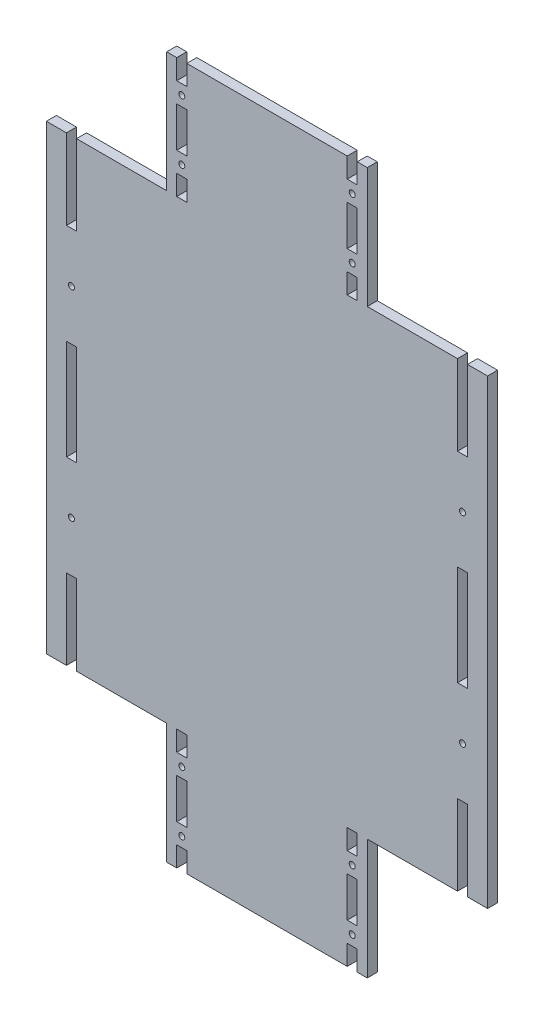
SolidWorks part; units mm, degrees
ref_plane "Front Plane" through (0, 0, 0) normal (0, 0, 1) x (1, 0, 0)
ref_plane "Top Plane" through (0, 0, 0) normal (0, 1, 0) x (1, 0, 0)
ref_plane "Right Plane" through (0, 0, 0) normal (1, 0, 0) x (0, 0, -1)
sketch "Sketch1" plane through (0, 0, 0) normal (0, 0, 1) x (1, 0, 0)
  line L1 (-110, 175) -> (110, 175)
  line L2 (-110, 175) -> (-110, -175)
  line L3 (-110, -175) -> (110, -175)
  line L4 (110, 175) -> (110, -175)
  line L5 (-110, 175) -> (110, -175) construction
  line L6 (-110, -175) -> (110, 175) construction
  point P0 (0, 0)
  dimension "D1" = 220
  dimension "D2" = 350
extrude "Boss-Extrude1" add sketch "Sketch1" along normal blind 5
sketch "Sketch2" plane through (0, 0, 5) normal (0, 0, 1) x (1, 0, 0)
  line L0 (0, 175) -> (0, -175) construction
  line L1 (110, 175) -> (-110, 175) construction
  line L2 (-110, -175) -> (110, -175) construction
  line L3 (-110, 0) -> (110, 0) construction
  line L4 (-110, 175) -> (-110, -175) construction
  line L5 (110, -175) -> (110, 175) construction
  line L6 (-110, 115) -> (110, 115) construction
  line L7 (-110, -115) -> (110, -115) construction
  line L8 (-50, 175) -> (-50, -175) construction
  line L9 (50, 175) -> (50, -175) construction
  line L10 (-110, -115) -> (-50, -115)
  line L11 (-110, -175) -> (-110, -115)
  line L12 (110, -115) -> (50, -115)
  line L13 (50, -115) -> (50, -175)
  line L14 (50, -175) -> (110, -175)
  line L15 (110, -175) -> (110, -115)
  line L16 (50, 175) -> (50, 115)
  line L17 (50, 115) -> (110, 115)
  line L18 (110, 115) -> (110, 175)
  line L19 (110, 175) -> (50, 175)
  line L20 (-110, 175) -> (-50, 175)
  line L21 (-50, 175) -> (-50, 115)
  line L22 (-50, 115) -> (-110, 115)
  line L23 (-110, 115) -> (-110, 175)
  line L24 (-50, -115) -> (-50, -175)
  line L25 (-50, -175) -> (-110, -175)
  dimension "D1" = 60
  dimension "D2" = 60
  dimension "D3" = 60
  dimension "D4" = 60
extrude "Cut-Extrude2" cut sketch "Sketch2" against normal blind 5
sketch "Sketch3" plane through (0, 0, 5) normal (0, 0, 1) x (1, 0, 0)
  line L0 (0, 175) -> (0, -175) construction
  line L2 (-50, -175) -> (50, -175) construction
  line L27 (50, 175) -> (-50, 175) construction
  line L32 (-45, 175) -> (-45, -175) construction
  line L33 (45, 175) -> (45, -175) construction
  line L34 (-50, -115) -> (50, -115) construction
  line L35 (-50, 115) -> (50, 115) construction
  line L37 (-45, 175) -> (-40, 175)
  line L38 (-45, 175) -> (-45, 115)
  line L39 (-45, 115) -> (-40, 115)
  line L40 (-40, 175) -> (-40, 115)
  line L41 (45, 175) -> (40, 175)
  line L42 (45, 175) -> (45, 115)
  line L43 (45, 115) -> (40, 115)
  line L44 (40, 175) -> (40, 115)
  line L45 (-45, -175) -> (-40, -175)
  line L46 (-45, -175) -> (-45, -115)
  line L47 (-45, -115) -> (-40, -115)
  line L48 (-40, -175) -> (-40, -115)
  line L49 (45, -175) -> (40, -175)
  line L50 (45, -175) -> (45, -115)
  line L51 (45, -115) -> (40, -115)
  line L52 (40, -175) -> (40, -115)
  line L53 (-45, 175) -> (-40, 175)
  line L54 (-45, 175) -> (-45, 165)
  line L55 (-45, 165) -> (-40, 165)
  line L56 (-40, 175) -> (-40, 165)
  line L57 (-45, 155) -> (-40, 155)
  line L58 (-45, 155) -> (-45, 135)
  line L59 (-45, 135) -> (-40, 135)
  line L60 (-40, 155) -> (-40, 135)
  line L61 (-45, 125) -> (-40, 125)
  line L62 (-45, 125) -> (-45, 115)
  line L63 (-45, 115) -> (-40, 115)
  line L64 (-40, 125) -> (-40, 115)
  line L65 (40, 175) -> (45, 175)
  line L66 (40, 175) -> (40, 163.255)
  line L68 (45, 175) -> (45, 163.255)
  line L69 (40, 155) -> (45, 155)
  line L70 (40, 155) -> (40, 135)
  line L71 (40, 135) -> (45, 135)
  line L72 (45, 155) -> (45, 135)
  line L73 (40, 115) -> (45, 115)
  line L74 (40, 115) -> (40, 125)
  line L75 (40, 125) -> (45, 125)
  line L76 (45, 115) -> (45, 125)
  line L77 (40, 175) -> (45, 175)
  line L78 (40, 175) -> (40, 165)
  line L79 (40, 165) -> (45, 165)
  line L80 (45, 175) -> (45, 165)
  line L81 (-45, -115) -> (-40, -115)
  line L82 (-45, -115) -> (-45, -125)
  line L83 (-45, -125) -> (-40, -125)
  line L84 (-40, -115) -> (-40, -125)
  line L85 (-45, -135) -> (-40, -135)
  line L86 (-45, -135) -> (-45, -155)
  line L87 (-45, -155) -> (-40, -155)
  line L88 (-40, -135) -> (-40, -155)
  line L89 (-45, -175) -> (-40, -175)
  line L90 (-45, -175) -> (-45, -165)
  line L91 (-45, -165) -> (-40, -165)
  line L92 (-40, -175) -> (-40, -165)
  line L93 (40, -115) -> (45, -115)
  line L94 (40, -115) -> (40, -125)
  line L95 (40, -125) -> (45, -125)
  line L96 (45, -115) -> (45, -125)
  line L97 (40, -135) -> (45, -135)
  line L98 (40, -135) -> (40, -155)
  line L99 (40, -155) -> (45, -155)
  line L100 (45, -135) -> (45, -155)
  line L101 (40, -165) -> (45, -165)
  line L102 (40, -165) -> (40, -175)
  line L103 (40, -175) -> (45, -175)
  line L104 (45, -165) -> (45, -175)
  line M9 (50, 175) -> (-50, 175)
  line M15 (-50, -175) -> (50, -175)
  dimension "D1" = 5
  dimension "D2" = 5
  dimension "D3" = 5
  dimension "D4" = 10
  dimension "D5" = 10
  dimension "D6" = 10
  dimension "D7" = 10
  dimension "D8" = 10
  dimension "5" = 5
  dimension "D9" = 10
  dimension "D10" = 10
  dimension "D11" = 10
extrude "Cut-Extrude3" cut sketch "Sketch3" against normal blind 5 contours L44 L79 L42 M9 | L44 L71 L42 L69 | L75 L44 L43 L42 | L38 L55 L40 M9 | L38 L59 L40 L57 | L61 L38 L39 L40 | L52 L95 L50 L51 | L52 L99 L50 L97 | L101 L52 L50 M15 | L46 L83 L48 L47 | L46 L87 L48 L85 | L91 L46 L48 M15
sketch "Sketch4" plane through (0, 0, 5) normal (0, 0, 1) x (1, 0, 0)
  line L0 (0, 175) -> (0, -175) construction
  line L1 (40, 175) -> (-40, 175) construction
  line L2 (-40, -175) -> (40, -175) construction
  line L3 (-50, 160) -> (50, 160) construction
  line L4 (-50, 115) -> (-50, 175) construction
  line L5 (50, 175) -> (50, 115) construction
  line L6 (-50, 130) -> (50, 130) construction
  line L7 (-42.5, 165) -> (-42.5, 125) construction
  line L8 (-45, 165) -> (-40, 165) construction
  line L9 (-45, 125) -> (-40, 125) construction
  line L10 (42.5, 165) -> (42.5, 125) construction
  line L11 (40, 165) -> (45, 165) construction
  line L12 (40, 125) -> (45, 125) construction
  line L13 (-50, -130) -> (50, -130) construction
  line L14 (-50, -175) -> (-50, -115) construction
  line L15 (50, -115) -> (50, -175) construction
  line L16 (-50, -160) -> (50, -160) construction
  line L17 (-42.5, -125) -> (-42.5, -165) construction
  line L20 (42.5, -125) -> (42.5, -165) construction
  line L21 (40, -125) -> (45, -125) construction
  line L22 (40, -165) -> (45, -165) construction
  line L23 (-45, -125) -> (-40, -125) construction
  line L24 (-45, -165) -> (-40, -165) construction
  circle A1 centre (-42.5, 160) radius 1.5
  circle A2 centre (42.5, 160) radius 1.5
  circle A3 centre (-42.5, 130) radius 1.5
  circle A4 centre (42.5, 130) radius 1.5
  circle A6 centre (-42.5, -160) radius 1.5
  circle A7 centre (-42.5, -130) radius 1.5
  circle A8 centre (42.5, -130) radius 1.5
  circle A9 centre (42.5, -160) radius 1.5
  dimension "D3" = 3
  dimension "D5" = 3
  dimension "D6" = 3
  dimension "D11" = 5
  dimension "D12" = 3
  dimension "D14" = 3
  dimension "D15" = 3
  dimension "D1" = 5
  dimension "D2" = 5
  dimension "D4" = 5
  dimension "D7" = 5
  dimension "D8" = 5
  dimension "D9" = 5
  dimension "D10" = 5
  dimension "D13" = 5
  dimension "D16" = 5
  dimension "D17" = 5
extrude "Cut-Extrude4" cut sketch "Sketch4" against normal blind 5
sketch "Sketch5" plane through (0, 0, 5) normal (0, 0, 1) x (1, 0, 0)
  line L0 (-100, 115) -> (-100, -115) construction
  line L1 (-110, 115) -> (-50, 115) construction
  line L2 (-50, -115) -> (-110, -115) construction
  line L3 (100, 115) -> (100, -115) construction
  line L4 (50, 115) -> (110, 115) construction
  line L5 (110, -115) -> (50, -115) construction
  line L7 (-100, 115) -> (-95, 115)
  line L8 (-100, 115) -> (-100, -115)
  line L9 (-100, -115) -> (-95, -115)
  line L10 (-95, 115) -> (-95, -115)
  line L11 (100, 115) -> (95, 115)
  line L12 (100, 115) -> (100, -115)
  line L13 (100, -115) -> (95, -115)
  line L14 (95, 115) -> (95, -115)
  line L15 (-100, 115) -> (-95, 115)
  line L16 (-100, 115) -> (-100, 75)
  line L17 (-100, 75) -> (-95, 75)
  line L18 (-95, 115) -> (-95, 75)
  line L19 (-100, 25) -> (-95, 25)
  line L20 (-100, 25) -> (-100, -25)
  line L21 (-100, -25) -> (-95, -25)
  line L22 (-95, 25) -> (-95, -25)
  line L23 (-100, -115) -> (-95, -115)
  line L24 (-100, -115) -> (-100, -75)
  line L25 (-100, -75) -> (-95, -75)
  line L26 (-95, -115) -> (-95, -75)
  line L27 (95, 115) -> (100, 115)
  line L28 (95, 115) -> (95, 75)
  line L29 (95, 75) -> (100, 75)
  line L30 (100, 115) -> (100, 75)
  line L31 (95, 25) -> (100, 25)
  line L32 (95, 25) -> (95, -25)
  line L33 (95, -25) -> (100, -25)
  line L34 (100, 25) -> (100, -25)
  line L35 (95, -115) -> (100, -115)
  line L36 (95, -115) -> (95, -75)
  line L37 (95, -75) -> (100, -75)
  line L38 (100, -115) -> (100, -75)
  dimension "D1" = 10
  dimension "D2" = 10
  dimension "D3" = 5
  dimension "D4" = 5
  dimension "D5" = 40
  dimension "D6" = 50
  dimension "D7" = 50
  dimension "D8" = 40
extrude "Cut-Extrude5" cut sketch "Sketch5" against normal blind 5 contours L25 L8 L9 L10 | L8 L21 L10 L19 | L8 L17 L10 L7 | L14 L29 L12 L11 | L14 L33 L12 L31 | L37 L14 L13 L12
sketch "Sketch6" plane through (0, 0, 5) normal (0, 0, 1) x (1, 0, 0)
  line L0 (-97.5, 75) -> (-97.5, -75) construction
  line L1 (-100, 75) -> (-95, 75) construction
  line L2 (-100, -75) -> (-95, -75) construction
  line L3 (97.5, 75) -> (97.5, -75) construction
  line L5 (-110, 50) -> (110, 50) construction
  line L6 (-110, 115) -> (-110, -115) construction
  line L7 (110, -115) -> (110, 115) construction
  line L8 (-110, -50) -> (110, -50) construction
  line L9 (95, 75) -> (100, 75) construction
  line L10 (95, -75) -> (100, -75) construction
  circle A0 centre (-97.5, 50) radius 1.5
  circle A1 centre (-97.5, -50) radius 1.5
  circle A2 centre (97.5, 50) radius 1.5
  circle A3 centre (97.5, -50) radius 1.5
  dimension "D3" = 3
  dimension "D4" = 3
  dimension "D5" = 3
  dimension "D6" = 3
  dimension "D1" = 25
  dimension "D2" = 25
  dimension "D7" = 25
  dimension "D8" = 25
  dimension "D9" = 25
  dimension "D10" = 25
extrude "Cut-Extrude6" cut sketch "Sketch6" against normal blind 5
